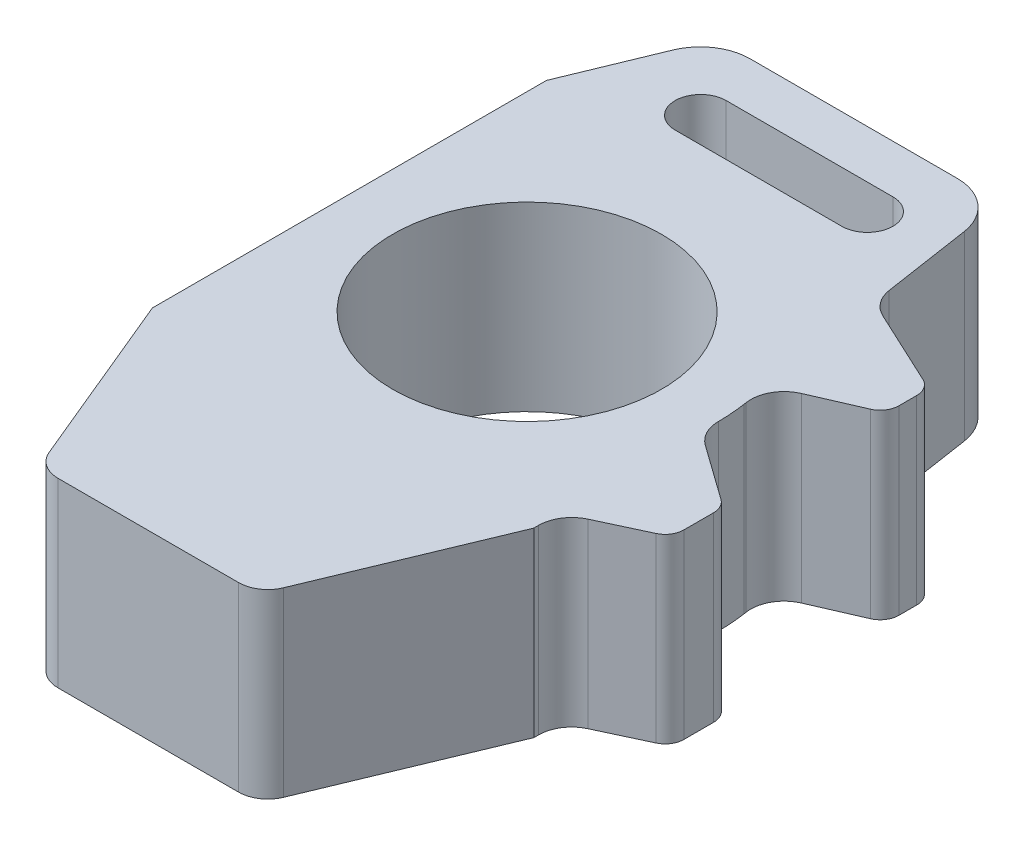
SolidWorks part; units mm, degrees
material "Custom Plastic"
ref_plane "X-Y Datum" through (0, 0, 0) normal (0, 0, 1) x (1, 0, 0)
ref_plane "X-Z Datum" through (0, 0, 0) normal (0, 1, 0) x (1, 0, 0)
ref_plane "Y-Z Datum" through (0, 0, 0) normal (1, 0, 0) x (0, 0, -1)
sketch "Sketch1" plane through (0, 0, 0) normal (0, 1, 0) x (1, 0, 0)
  line L23 (-33.3761, -108.9566) -> (-55.5625, -55.5625) construction
  line L25 (-55.5625, -54.5696) -> (-55.5625, -55.5625) construction
  line L26 (-55.5625, 63.5) -> (-55.5625, -54.5696) construction
  line L27 (-44.5126, 90.3478) -> (-55.5625, 63.5) construction
  line L30 (-32.7684, 98.2142) -> (30.3592, 98.2142) construction
  line L31 (47.017, 60.43) -> (42.915, 87.4223) construction
  line L32 (54.2056, 50.8279) -> (77.0794, 40.1617) construction
  line L35 (78.9125, 37.2842) -> (78.9125, 31.8633) construction
  line L36 (77.0039, 28.9517) -> (62.3214, 22.5657) construction
  line L49 (54.9318, 8.3479) -> (54.831, 9.0115) construction
  line L51 (60.8833, -10.1158) -> (77.5822, -22.0366) construction
  line L52 (78.9125, -24.6207) -> (78.9125, -33.6635) construction
  line L55 (77.0794, -36.5411) -> (62.8952, -43.1552) construction
  line L56 (55.5625, -55.5625) -> (55.5625, -54.6653) construction
  line L57 (55.5625, -55.5625) -> (33.3761, -108.9566) construction
  line L58 (-27.5122, -112.87) -> (27.5122, -112.87) construction
  line L59 (-33.3761, -108.9566) -> (-55.5625, -55.5625) construction
  line L60 (-55.5625, -54.5696) -> (-55.5625, -55.5625) construction
  line L61 (-55.5625, 63.5) -> (-55.5625, -54.5696) construction
  line L62 (-44.5126, 90.3478) -> (-55.5625, 63.5) construction
  line L63 (-32.7684, 98.2142) -> (30.3592, 98.2142) construction
  line L64 (47.017, 60.43) -> (42.915, 87.4223) construction
  line L65 (54.2056, 50.8279) -> (77.0794, 40.1617) construction
  line L66 (78.9125, 37.2842) -> (78.9125, 31.8633) construction
  line L67 (77.0039, 28.9517) -> (62.3214, 22.5657) construction
  line L68 (54.9318, 8.3479) -> (54.831, 9.0115) construction
  line L69 (60.8833, -10.1158) -> (77.5822, -22.0366) construction
  line L70 (78.9125, -24.6207) -> (78.9125, -33.6635) construction
  line L71 (77.0794, -36.5411) -> (62.8952, -43.1552) construction
  line L72 (55.5625, -55.5625) -> (55.5625, -54.6653) construction
  line L73 (55.5625, -55.5625) -> (33.3761, -108.9566) construction
  line L74 (-27.5122, -112.87) -> (27.5122, -112.87) construction
  line L75 (-35.7217, -109.9312) -> (-58.1025, -56.0692)
  line L76 (-58.1025, -54.5696) -> (-58.1025, -56.0692)
  line L77 (-58.1025, 64.0023) -> (-58.1025, -54.5696)
  line L78 (-46.8614, 91.3145) -> (-58.1025, 64.0023)
  line L79 (-32.7684, 100.7542) -> (30.3592, 100.7542)
  line L80 (49.5282, 60.8116) -> (45.4262, 87.8039)
  line L81 (55.279, 53.13) -> (78.1528, 42.4638)
  line L82 (81.4525, 37.2842) -> (81.4525, 31.8633)
  line L83 (78.017, 26.6225) -> (63.3345, 20.2365)
  line L84 (57.443, 8.7295) -> (57.3421, 9.3931)
  line L85 (62.3591, -8.0485) -> (79.058, -19.9693)
  line L86 (81.4525, -24.6207) -> (81.4525, -33.6635)
  line L87 (78.1528, -38.8431) -> (63.9687, -45.4572)
  line L88 (58.1025, -56.0692) -> (58.1025, -54.6653)
  line L89 (58.1025, -56.0692) -> (35.7217, -109.9312)
  line L90 (-27.5122, -115.41) -> (27.5122, -115.41)
  arc A28 (-32.7684, 98.2142) -> (-44.5126, 90.3478) centre (-32.7684, 85.5142) ccw construction
  arc A29 (42.915, 87.4223) -> (30.3592, 98.2142) centre (30.3592, 85.5142) ccw construction
  arc A34 (47.017, 60.43) -> (54.2056, 50.8279) centre (59.5728, 62.3381) ccw construction
  arc A35 (78.9125, 37.2842) -> (77.0794, 40.1617) centre (75.7375, 37.2842) ccw construction
  arc A36 (77.0039, 28.9517) -> (78.9125, 31.8633) centre (75.7375, 31.8633) ccw construction
  arc A37 (62.3214, 22.5657) -> (54.831, 9.0115) centre (67.3868, 10.9196) ccw construction
  arc A38 (55.5622, 0.1796) -> (54.9318, 8.3479) centre (0, 0) ccw construction
  arc A39 (55.5622, 0.1796) -> (60.8833, -10.1158) centre (68.2621, 0.2207) ccw construction
  arc A40 (78.9125, -24.6207) -> (77.5822, -22.0366) centre (75.7375, -24.6207) ccw construction
  arc A41 (77.0794, -36.5411) -> (78.9125, -33.6635) centre (75.7375, -33.6635) ccw construction
  arc A42 (62.8952, -43.1552) -> (55.5629, -54.5696) centre (68.2625, -54.6653) ccw construction
  arc A43 (55.5629, -54.5696) -> (55.5625, -54.6653) centre (68.2625, -54.6653) ccw construction
  arc A44 (27.5122, -112.87) -> (33.3761, -108.9566) centre (27.5122, -106.52) ccw construction
  arc A45 (-33.3761, -108.9566) -> (-27.5122, -112.87) centre (-27.5122, -106.52) ccw construction
  arc A46 (-32.7684, 98.2142) -> (-44.5126, 90.3478) centre (-32.7684, 85.5142) ccw construction
  arc A47 (42.915, 87.4223) -> (30.3592, 98.2142) centre (30.3592, 85.5142) ccw construction
  arc A48 (47.017, 60.43) -> (54.2056, 50.8279) centre (59.5728, 62.3381) ccw construction
  arc A49 (78.9125, 37.2842) -> (77.0794, 40.1617) centre (75.7375, 37.2842) ccw construction
  arc A50 (77.0039, 28.9517) -> (78.9125, 31.8633) centre (75.7375, 31.8633) ccw construction
  arc A51 (62.3214, 22.5657) -> (54.831, 9.0115) centre (67.3868, 10.9196) ccw construction
  arc A52 (55.5622, 0.1796) -> (54.9318, 8.3479) centre (0, 0) ccw construction
  arc A53 (55.5622, 0.1796) -> (60.8833, -10.1158) centre (68.2621, 0.2207) ccw construction
  arc A54 (78.9125, -24.6207) -> (77.5822, -22.0366) centre (75.7375, -24.6207) ccw construction
  arc A55 (77.0794, -36.5411) -> (78.9125, -33.6635) centre (75.7375, -33.6635) ccw construction
  arc A56 (62.8952, -43.1552) -> (55.5629, -54.5696) centre (68.2625, -54.6653) ccw construction
  arc A57 (55.5629, -54.5696) -> (55.5625, -54.6653) centre (68.2625, -54.6653) ccw construction
  arc A58 (27.5122, -112.87) -> (33.3761, -108.9566) centre (27.5122, -106.52) ccw construction
  arc A59 (-33.3761, -108.9566) -> (-27.5122, -112.87) centre (-27.5122, -106.52) ccw construction
  arc A60 (-32.7684, 100.7542) -> (-46.8614, 91.3145) centre (-32.7684, 85.5142) ccw
  arc A61 (45.4262, 87.8039) -> (30.3592, 100.7542) centre (30.3592, 85.5142) ccw
  arc A62 (49.5282, 60.8116) -> (55.279, 53.13) centre (59.5728, 62.3381) ccw
  arc A63 (81.4525, 37.2842) -> (78.1528, 42.4638) centre (75.7375, 37.2842) ccw
  arc A64 (78.017, 26.6225) -> (81.4525, 31.8633) centre (75.7375, 31.8633) ccw
  arc A65 (63.3345, 20.2365) -> (57.3421, 9.3931) centre (67.3868, 10.9196) ccw
  arc A66 (58.1022, 0.1878) -> (57.443, 8.7295) centre (0, 0) ccw
  arc A67 (58.1022, 0.1878) -> (62.3591, -8.0485) centre (68.2621, 0.2207) ccw
  arc A68 (81.4525, -24.6207) -> (79.058, -19.9693) centre (75.7375, -24.6207) ccw
  arc A69 (78.1528, -38.8431) -> (81.4525, -33.6635) centre (75.7375, -33.6635) ccw
  arc A70 (63.9687, -45.4572) -> (58.1028, -54.5887) centre (68.2625, -54.6653) ccw
  arc A71 (58.1028, -54.5887) -> (58.1025, -54.6653) centre (68.2625, -54.6653) ccw
  arc A72 (27.5122, -115.41) -> (35.7217, -109.9312) centre (27.5122, -106.52) ccw
  arc A73 (-35.7217, -109.9312) -> (-27.5122, -115.41) centre (-27.5122, -106.52) ccw
  dimension "D1" = 2.54
extrude "Boss-Extrude1" add sketch "Sketch1" along normal offset from surface 2.54 and the other way offset from surface (27.084 mm away) 2.54
sketch "Sketch2" plane through (0, 28.227, 0) normal (0, 1, 0) x (1, 0, 0)
  circle A0 centre (0, 0) radius 43.4975 construction
  circle A1 centre (0, 0) radius 43.4975 construction
  circle A2 centre (0, 0) radius 40.9575
  dimension "D1" = 2.54
extrude "Cut-Extrude1" cut sketch "Sketch2" against normal through all
sketch "Sketch3" plane through (0, 28.227, 0) normal (0, 1, 0) x (1, 0, 0)
  line L0 (25.4, 88.6186) -> (-25.4, 88.6186) construction
  line L1 (-25.4, 67.9684) -> (25.4, 67.9684) construction
  line L2 (25.4, 88.6186) -> (-25.4, 88.6186) construction
  line L3 (-25.4, 67.9684) -> (25.4, 67.9684) construction
  line L4 (25.4, 86.0786) -> (-25.4, 86.0786)
  line L5 (-25.4, 70.5084) -> (25.4, 70.5084)
  arc A0 (-25.4, 88.6186) -> (-28.7189, 68.5163) centre (-25.4, 78.2935) ccw construction
  arc A1 (-28.7189, 68.5163) -> (-25.4, 67.9684) centre (-25.4, 78.2935) ccw construction
  arc A2 (25.4, 67.9684) -> (28.7189, 68.5163) centre (25.4, 78.2935) ccw construction
  arc A3 (28.7189, 68.5163) -> (25.4, 88.6186) centre (25.4, 78.2935) ccw construction
  arc A4 (-25.4, 88.6186) -> (-28.7189, 68.5163) centre (-25.4, 78.2935) ccw construction
  arc A5 (-28.7189, 68.5163) -> (-25.4, 67.9684) centre (-25.4, 78.2935) ccw construction
  arc A6 (25.4, 67.9684) -> (28.7189, 68.5163) centre (25.4, 78.2935) ccw construction
  arc A7 (28.7189, 68.5163) -> (25.4, 88.6186) centre (25.4, 78.2935) ccw construction
  arc A8 (-25.4, 86.0786) -> (-27.9025, 70.9215) centre (-25.4, 78.2935) ccw
  arc A9 (-27.9025, 70.9215) -> (-25.4, 70.5084) centre (-25.4, 78.2935) ccw
  arc A10 (25.4, 70.5084) -> (27.9025, 70.9215) centre (25.4, 78.2935) ccw
  arc A11 (27.9025, 70.9215) -> (25.4, 86.0786) centre (25.4, 78.2935) ccw
  dimension "D1" = 2.54
extrude "Cut-Extrude2" cut sketch "Sketch3" against normal through all contours L5 A10 A11 L4 A8 A9
